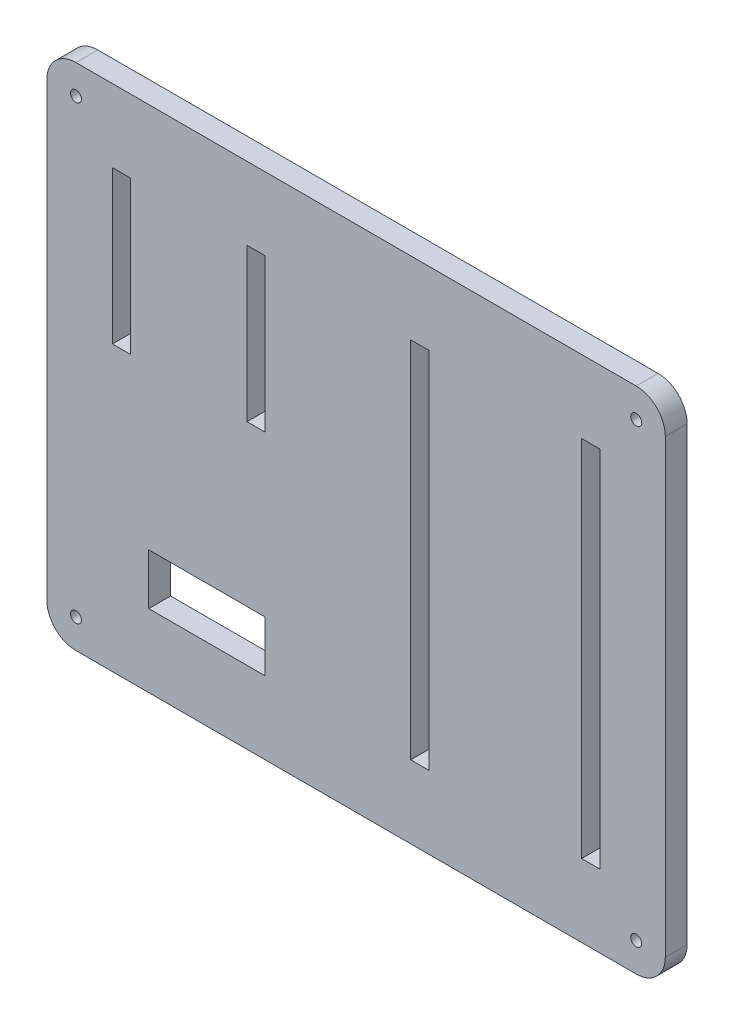
SolidWorks part; units mm, degrees
ref_plane "Front Plane" through (0, 0, 0) normal (0, 0, 1) x (1, 0, 0)
ref_plane "Top Plane" through (0, 0, 0) normal (0, 1, 0) x (1, 0, 0)
ref_plane "Right Plane" through (0, 0, 0) normal (1, 0, 0) x (0, 0, -1)
sketch "Sketch1" plane through (0, 0, 0) normal (0, 0, 1) x (1, 0, 0)
  line L1 (-42.5, 35) -> (42.5, 35)
  line L2 (-42.5, 35) -> (-42.5, -35)
  line L3 (-42.5, -35) -> (42.5, -35)
  line L4 (42.5, 35) -> (42.5, -35)
  line L5 (-42.5, 35) -> (42.5, -35) construction
  line L6 (-42.5, -35) -> (42.5, 35) construction
  point P0 (0, 0)
  dimension "D1" = 85
  dimension "D2" = 70
extrude "Boss-Extrude1" add sketch "Sketch1" along normal blind 3
sketch "Sketch2" plane through (0, 0, 0) normal (0, 0, -1) x (-1, 0, 0)
  line L0 (-33.5, 25) -> (-33.5, -25)
  line L1 (-33.5, 25) -> (-7.5, 25)
  line L2 (-33.5, -25) -> (-7.5, -25)
  line L3 (-7.5, 25) -> (-7.5, -25)
  line L4 (-31, 25) -> (-31, -25)
  line L5 (-10, 25) -> (-10, -25)
  line L6 (42.5, -35) -> (-42.5, -35) construction
  line L7 (12.5, 25) -> (12.5, 4)
  line L8 (12.5, 25) -> (33.5, 25)
  line L9 (12.5, 4) -> (33.5, 4)
  line L10 (33.5, 25) -> (33.5, 4)
  line L11 (12.5, -18) -> (28.5, -18)
  line L12 (12.5, -18) -> (12.5, -25)
  line L13 (28.5, -18) -> (28.5, -25)
  line L14 (12.5, -25) -> (28.5, -25)
  line L17 (-42.5, 35) -> (42.5, 35) construction
  line L18 (15, 25) -> (15, 4)
  line L19 (31, 25) -> (31, 4)
  line L20 (-42.5, -35) -> (-42.5, 35) construction
  dimension "D1" = 26
  dimension "D2" = 2.5
  dimension "D3" = 2.5
  dimension "D4" = 50
  dimension "D5" = 10
  dimension "D6" = 21
  dimension "D7" = 21
  dimension "D8" = 16
  dimension "D9" = 7
  dimension "D10" = 22
  dimension "D11" = 10
  dimension "D12" = 2.5
  dimension "D13" = 2.5
  dimension "D14" = 20
  dimension "D15" = 9
  dimension "D16" = 20
extrude "Cut-Extrude1" cut sketch "Sketch2" against normal through all contours L4 L1 L0 L2 | L1 L5 L2 L3 | L18 L8 L7 L9 | L8 L19 L9 L10 | L12 L14 L13 L11
fillet "Fillet1" radius 4 4 edges at (42.5, 35, 1.5) (-42.5, 35, 1.5) (-42.5, -35, 1.5) (42.5, -35, 1.5)
sketch "Sketch4" plane through (0, 0, 0) normal (0, 0, -1) x (-1, 0, 0)
  line L0 (0, 35) -> (0, -35) construction
  line L1 (-38.5, 35) -> (38.5, 35) construction
  line L2 (38.5, -35) -> (-38.5, -35) construction
  line L3 (-42.5, 0) -> (42.5, 0) construction
  line L4 (-42.5, -31) -> (-42.5, 31) construction
  line L5 (42.5, 31) -> (42.5, -31) construction
  circle A0 centre (-38.5, 31) radius 4
  circle A1 centre (-38.5, 31) radius 0.75
  circle A2 centre (38.5, 31) radius 0.75
  circle A3 centre (38.5, 31) radius 4
  circle A4 centre (38.5, -31) radius 0.75
  circle A5 centre (38.5, -31) radius 4
  circle A6 centre (-38.5, -31) radius 0.75
  circle A7 centre (-38.5, -31) radius 4
  dimension "D1" = 8
  dimension "D2" = 1.5
extrude "Cut-Extrude3" cut sketch "Sketch4" against normal blind 10 contours A1 | A2 | A4 | A6
